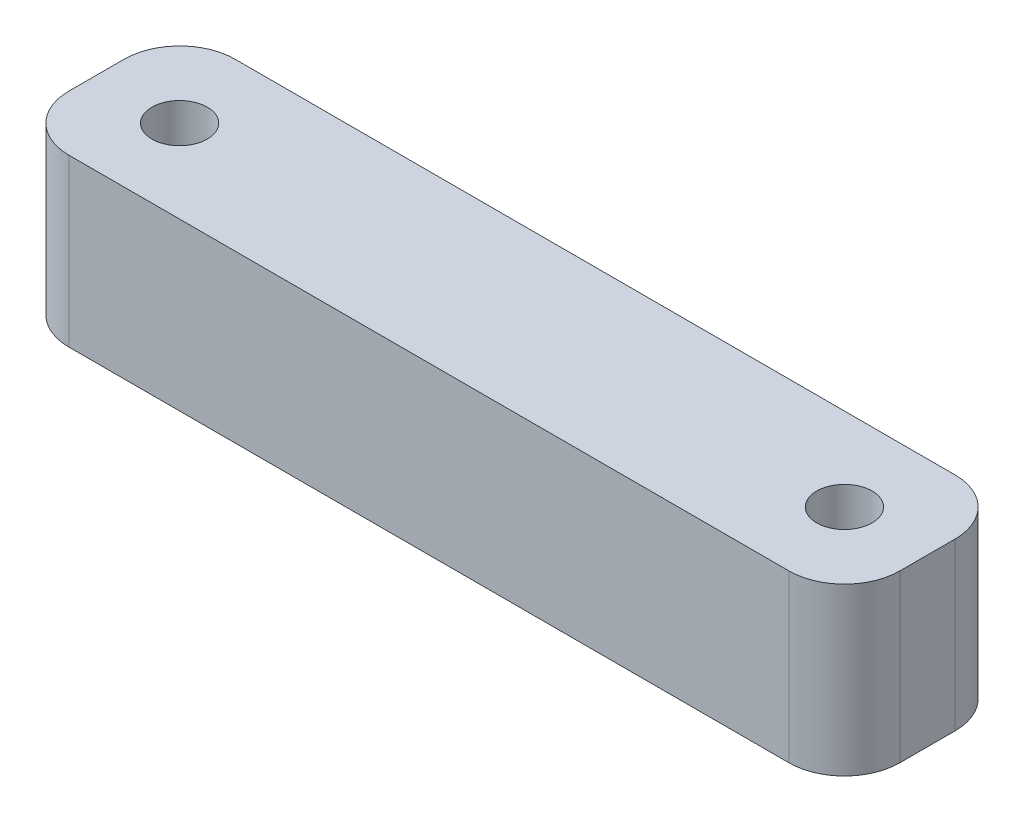
SolidWorks part; units mm, degrees
ref_plane "Front Plane" through (0, 0, 0) normal (0, 0, 1) x (1, 0, 0)
ref_plane "Top Plane" through (0, 0, 0) normal (0, 1, 0) x (1, 0, 0)
ref_plane "Right Plane" through (0, 0, 0) normal (1, 0, 0) x (0, 0, -1)
sketch "Sketch1" plane through (0, 0, 0) normal (0, 1, 0) x (1, 0, 0)
  line L0 (0, 0) -> (0, -15) construction
  line L1 (-45, -15) -> (45, -15)
  line L2 (-45, -15) -> (-45, 15)
  line L3 (-45, 15) -> (45, 15)
  line L4 (45, -15) -> (45, 15)
  line L5 (-45, -15) -> (45, 15) construction
  line L6 (-45, 15) -> (45, -15) construction
  line L7 (45, 15) -> (75, 15)
  line L8 (45, 15) -> (45, -15)
  line L9 (45, -15) -> (75, -15)
  line L10 (75, 15) -> (75, -15)
  line L11 (45, 15) -> (75, -15) construction
  line L12 (45, -15) -> (75, 15) construction
  line L13 (-45, -15) -> (-75, -15)
  line L14 (-75, 15) -> (-75, -15)
  line L15 (-45, 15) -> (-75, 15)
  line L16 (-45, 15) -> (-45, -15)
  circle A0 centre (60, 0) radius 5
  circle A1 centre (-60, 0) radius 5
  point P0 (0, 0)
  point P8 (60, 0)
  dimension "D4" = 10
  dimension "D1" = 90
  dimension "D2" = 30
  dimension "D3" = 30
extrude "Boss-Extrude1" add sketch "Sketch1" along normal blind 30 contours L1 L4 L3 L2 | L10 L7 L4 L9 A0 | L2 L15 L14 L13 A1
fillet "Fillet1" radius 10 4 edges at (-75, 15, -15) (-75, 15, 15) (75, 15, -15) (75, 15, 15)
